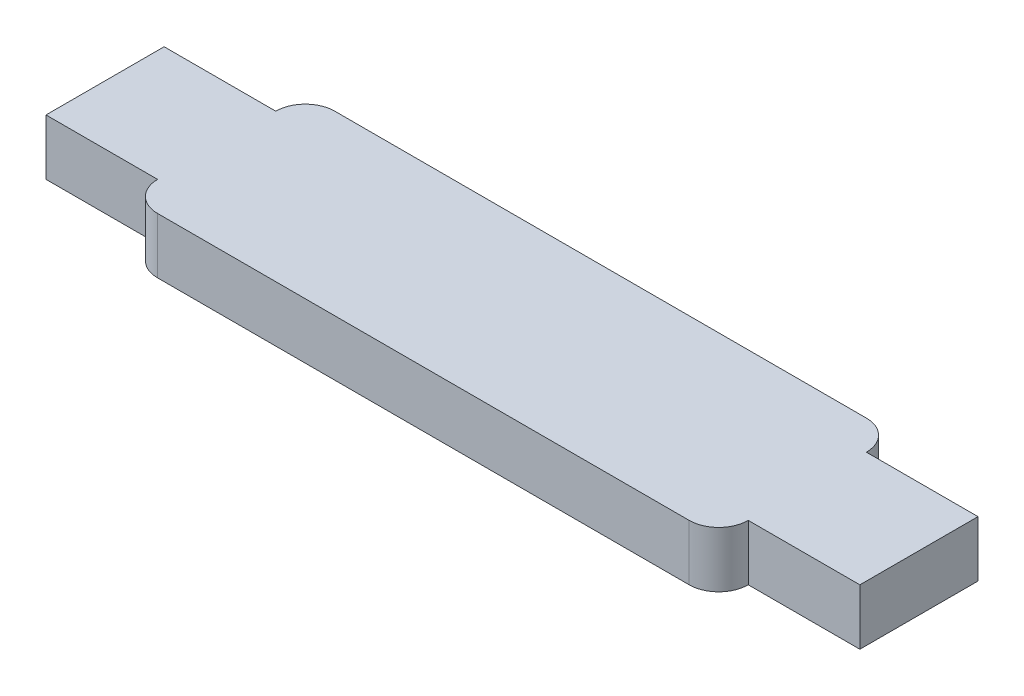
SolidWorks part; units mm, degrees
ref_plane "Front Plane" through (0, 0, 0) normal (0, 0, 1) x (1, 0, 0)
ref_plane "Top Plane" through (0, 0, 0) normal (0, 1, 0) x (1, 0, 0)
ref_plane "Right Plane" through (0, 0, 0) normal (1, 0, 0) x (0, 0, -1)
sketch "Sketch1" plane through (0, 0, 0) normal (0, 1, 0) x (1, 0, 0)
  line L1 (14.2875, -4.7625) -> (-14.2875, -4.7625)
  line L2 (15.875, -3.175) -> (15.875, 3.175)
  line L3 (14.2875, 4.7625) -> (-14.2875, 4.7625)
  line L4 (-15.875, -3.175) -> (-15.875, 3.175)
  line L5 (15.875, -4.7625) -> (-15.875, 4.7625) construction
  line L6 (15.875, 4.7625) -> (-15.875, -4.7625) construction
  arc A0 (15.875, 3.175) -> (14.2875, 4.7625) centre (14.2875, 3.175) ccw
  arc A1 (15.875, -3.175) -> (14.2875, -4.7625) centre (14.2875, -3.175) cw
  arc A2 (-14.2875, -4.7625) -> (-15.875, -3.175) centre (-14.2875, -3.175) cw
  arc A3 (-14.2875, 4.7625) -> (-15.875, 3.175) centre (-14.2875, 3.175) ccw
  point P0 (0, 0)
  dimension "D3" = 1.5875
  dimension "D1" = 31.75
  dimension "D2" = 9.525
extrude "Boss-Extrude1" add sketch "Sketch1" along normal mid plane 3
sketch "Sketch2" plane through (0, 1.5, 0) normal (0, 1, 0) x (1, 0, 0)
  line L0 (-15.875, 3.175) -> (-15.875, -3.175) construction
  line L1 (-21.875, -3.175) -> (-15.875, -3.175)
  line L2 (-21.875, -3.175) -> (-21.875, 3.175)
  line L3 (-21.875, 3.175) -> (-15.875, 3.175)
  line L4 (-15.875, -3.175) -> (-15.875, 3.175)
  line L5 (-21.875, -3.175) -> (-15.875, 3.175) construction
  line L6 (-21.875, 3.175) -> (-15.875, -3.175) construction
  point P0 (-18.875, 0)
  point P5 (0, 0)
  point P6 (0, 0)
  dimension "D1" = 6.35
  dimension "D2" = 6
extrude "Boss-Extrude2" add sketch "Sketch2" against normal up to surface (3 mm away) up to face at (0, -1.5, 0)
mirror "Mirror1" about plane through (0, 0, 0) normal (1, 0, 0) of "Boss-Extrude2"
